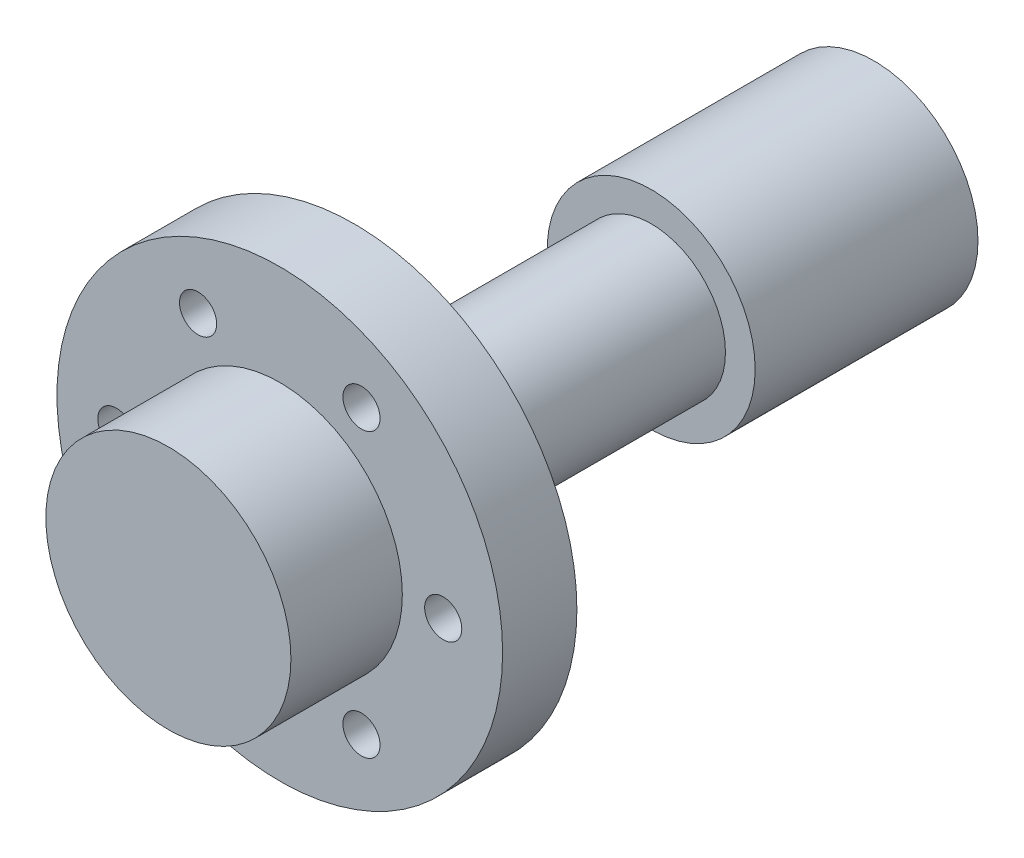
SolidWorks part; units mm, degrees
ref_plane "Piano frontale" through (0, 0, 0) normal (0, 0, 1) x (1, 0, 0)
ref_plane "Piano superiore" through (0, 0, 0) normal (0, 1, 0) x (1, 0, 0)
ref_plane "Piano destro" through (0, 0, 0) normal (1, 0, 0) x (0, 0, -1)
sketch "Schizzo1" plane through (0, 0, 0) normal (0, 0, 1) x (1, 0, 0)
  circle A0 centre (0, 0) radius 14
extrude "Estrusione-Estrusione1" add sketch "Schizzo1" along normal blind 30
sketch "Schizzo2" plane through (0, 0, 30) normal (0, 0, 1) x (1, 0, 0)
  circle A0 centre (0, 0) radius 10
extrude "Estrusione-Estrusione2" add sketch "Schizzo2" along normal blind 40
sketch "Schizzo3" plane through (0, 0, 70) normal (0, 0, 1) x (1, 0, 0)
  circle A0 centre (0, 0) radius 30
extrude "Estrusione-Estrusione3" add sketch "Schizzo3" along normal blind 10
sketch "Schizzo4" plane through (0, 0, 80) normal (0, 0, 1) x (1, 0, 0)
  circle A0 centre (0, 0) radius 16.5
extrude "Estrusione-Estrusione4" add sketch "Schizzo4" along normal blind 15
sketch "Schizzo5" plane through (0, 0, 0) normal (0, 0, -1) x (-1, 0, 0)
  circle A0 centre (0, 0) radius 7
extrude "Taglio-Estrusione1" cut sketch "Schizzo5" against normal blind 25
sketch "Schizzo6" plane through (0, 0, 80) normal (0, 0, 1) x (1, 0, 0)
  circle A0 centre (22, 0) radius 2.5
  circle A1 centre (11, 19.0526) radius 2.5
  circle A2 centre (-11, 19.0526) radius 2.5
  circle A3 centre (-22, 0) radius 2.5
  circle A4 centre (-11, -19.0526) radius 2.5
  circle A5 centre (11, -19.0526) radius 2.5
extrude "Taglio-Estrusione2" cut sketch "Schizzo6" against normal blind 10
